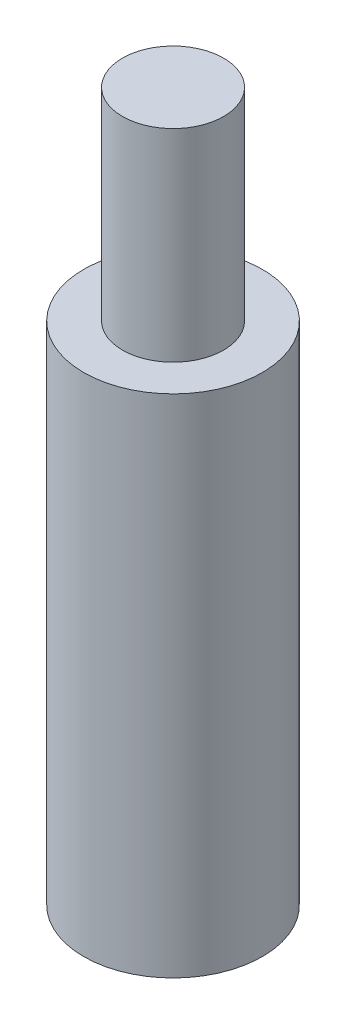
SolidWorks part; units mm, degrees
ref_plane "Front Plane" through (0, 0, 0) normal (0, 0, 1) x (1, 0, 0)
ref_plane "Top Plane" through (0, 0, 0) normal (0, 1, 0) x (1, 0, 0)
ref_plane "Right Plane" through (0, 0, 0) normal (1, 0, 0) x (0, 0, -1)
sketch "Sketch1" plane through (0, 0, 0) normal (0, 1, 0) x (1, 0, 0)
  circle A0 centre (0, 0) radius 2.65
  dimension "D1" = 5.3
extrude "Boss-Extrude1" add sketch "Sketch1" along normal blind 15
sketch "Sketch2" plane through (0, 15, 0) normal (0, 1, 0) x (1, 0, 0)
  circle A0 centre (0, 0) radius 1.5
  dimension "D1" = 3
extrude "Boss-Extrude2" add sketch "Sketch2" along normal blind 6
sketch "Sketch3" plane through (0, 0, 0) normal (0, -1, 0) x (1, 0, 0)
  circle A0 centre (0, 0) radius 1.5
  dimension "D1" = 3
extrude "Cut-Extrude1" cut sketch "Sketch3" against normal blind 10
